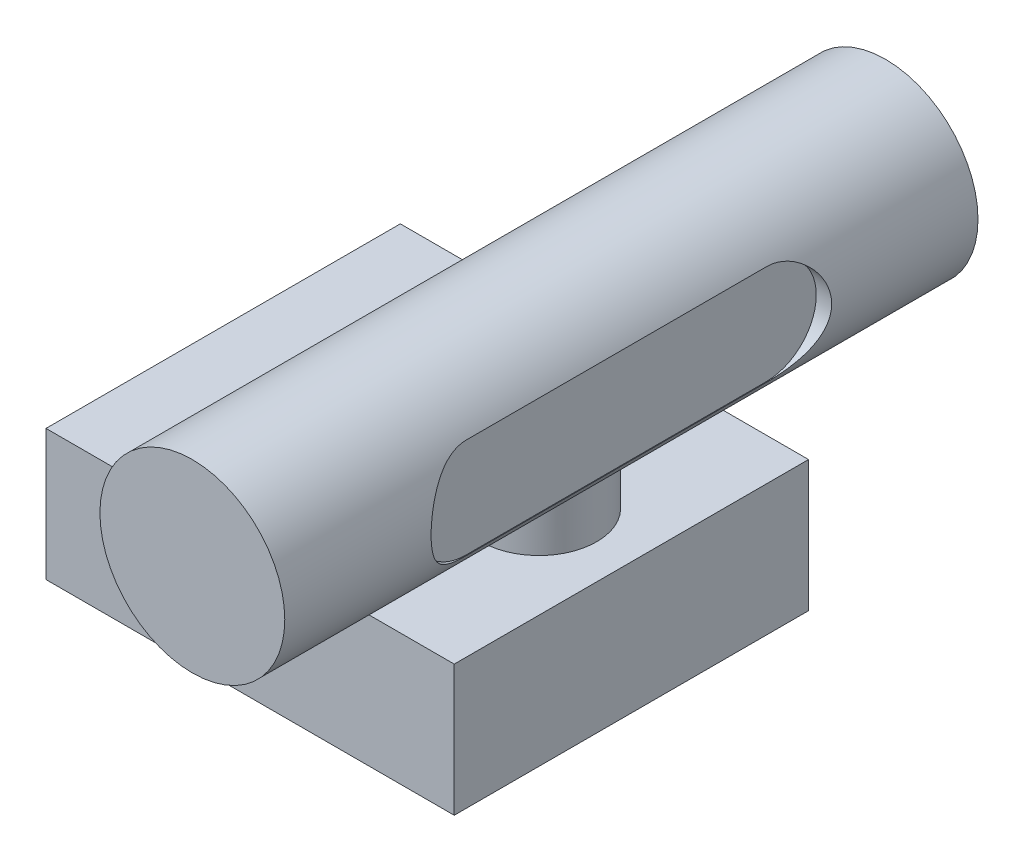
SolidWorks part; units mm, degrees
ref_plane "Front Plane" through (0, 0, 0) normal (0, 0, 1) x (1, 0, 0)
ref_plane "Top Plane" through (0, 0, 0) normal (0, 1, 0) x (1, 0, 0)
ref_plane "Right Plane" through (0, 0, 0) normal (1, 0, 0) x (0, 0, -1)
sketch "Sketch1" plane through (0, 0, 0) normal (0, 0, 1) x (1, 0, 0)
  circle A0 centre (0, 0) radius 12
  dimension "D1" = 24
extrude "Boss-Extrude1" add sketch "Sketch1" along normal mid plane 90
sketch "Sketch2" plane through (0, 0, 0) normal (0, 1, 0) x (1, 0, 0)
  circle A0 centre (0, 0) radius 7.5
  dimension "D1" = 15
extrude "Boss-Extrude2" add sketch "Sketch2" against normal blind 16
sketch "Sketch3" plane through (0, -16, 0) normal (0, -1, 0) x (1, 0, 0)
  line L0 (12, -45) -> (12, 45) construction
  line L1 (-41, -23) -> (12, -23)
  line L2 (-41, -23) -> (-41, 23)
  line L3 (-41, 23) -> (12, 23)
  line L4 (12, -23) -> (12, 23)
  line L5 (-41, -23) -> (12, 23) construction
  line L6 (-41, 23) -> (12, -23) construction
  point P0 (-14.5, 0)
  point P7 (0, 0)
  dimension "D1" = 46
  dimension "D2" = 53
extrude "Boss-Extrude3" add sketch "Sketch3" along normal blind 17
sketch "Sketch4" plane through (12, 0, 0) normal (1, 0, 0) x (0, 0, -1)
  line L0 (0, -6.5) -> (0, 6.5) construction
  line L1 (-19.5, 6.5) -> (19.5, 6.5)
  line L2 (19.5, -6.5) -> (-19.5, -6.5)
  arc A1 (19.5, 6.5) -> (19.5, -6.5) centre (19.5, 0) cw
  arc A2 (-19.5, 6.5) -> (-19.5, -6.5) centre (-19.5, 0) ccw
  point P5 (0, 0)
  point P12 (13, 0)
  point P13 (18.3351, 0)
  dimension "D1" = 26
  dimension "D2" = 13
extrude "Cut-Extrude1" cut sketch "Sketch4" against normal blind 2
